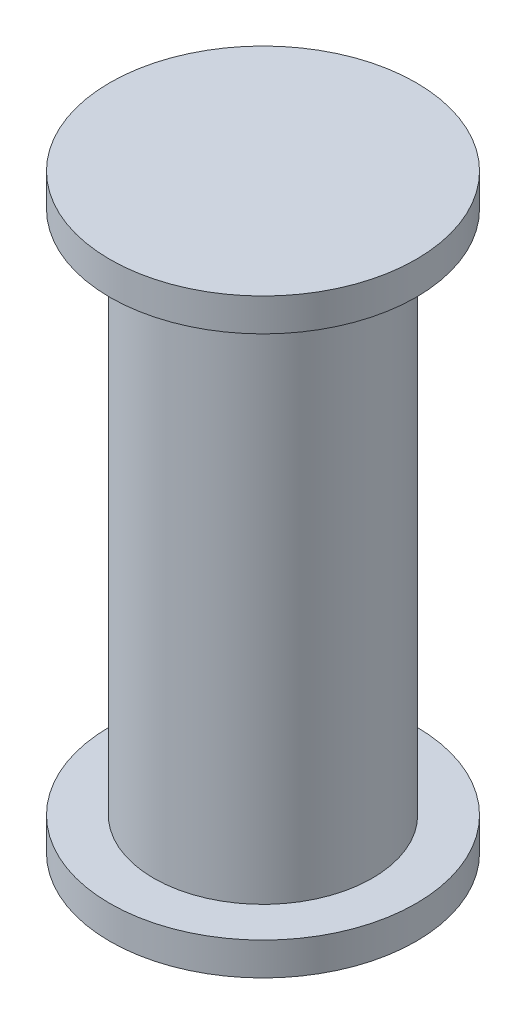
SolidWorks part; units mm, degrees
ref_plane "Front Plane" through (0, 0, 0) normal (0, 0, 1) x (1, 0, 0)
ref_plane "Top Plane" through (0, 0, 0) normal (0, 1, 0) x (1, 0, 0)
ref_plane "Right Plane" through (0, 0, 0) normal (1, 0, 0) x (0, 0, -1)
sketch "Sketch1" plane through (0, 0, 0) normal (0, 1, 0) x (1, 0, 0)
  circle A0 centre (0, 0) radius 5
  dimension "D1" = 10
extrude "Boss-Extrude1" add sketch "Sketch1" along normal mid plane 24
sketch "Sketch2" plane through (0, 12, 0) normal (0, 1, 0) x (1, 0, 0)
  circle A0 centre (0, 0) radius 7
extrude "Boss-Extrude2" add sketch "Sketch2" along normal blind 1.5
mirror "Mirror1" about plane through (0, 0, 0) normal (0, 1, 0) of "Boss-Extrude2"
